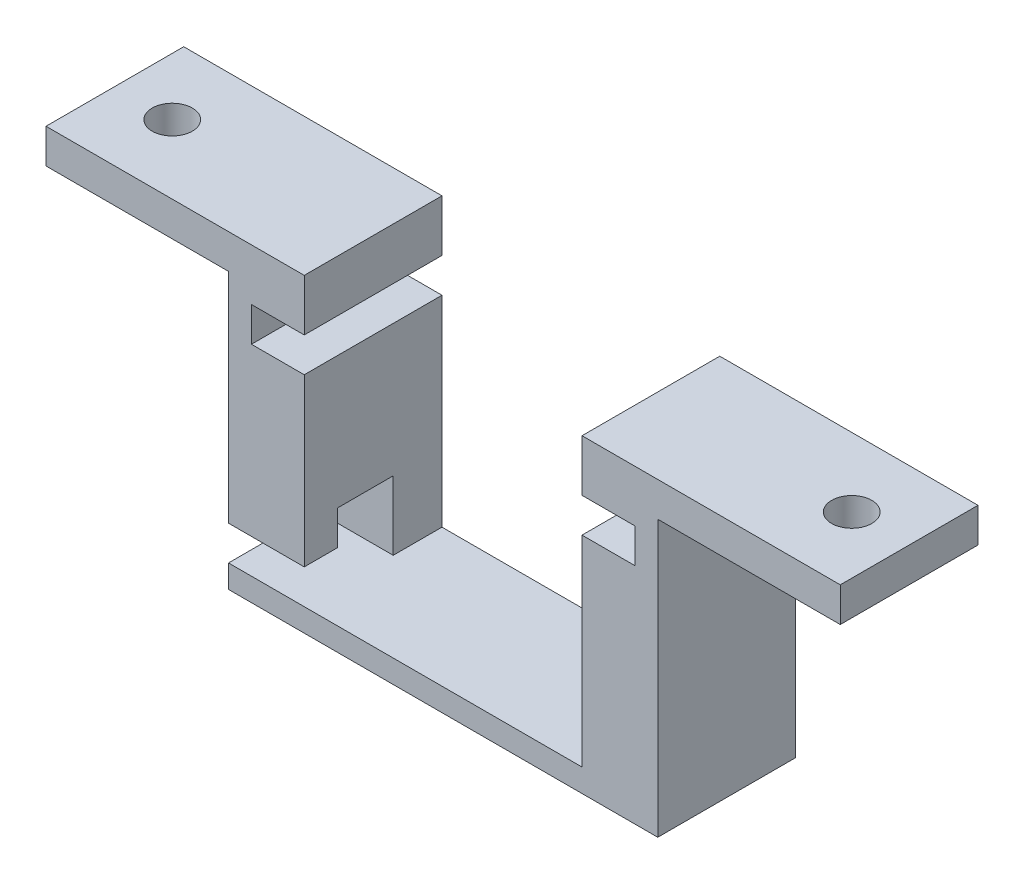
SolidWorks part; units mm, degrees
ref_plane "Alzado" through (0, 0, 0) normal (0, 0, 1) x (1, 0, 0)
ref_plane "Planta" through (0, 0, 0) normal (0, 1, 0) x (1, 0, 0)
ref_plane "Vista lateral" through (0, 0, 0) normal (1, 0, 0) x (0, 0, -1)
sketch "Croquis1" plane through (0, 0, 0) normal (0, 0, 1) x (1, 0, 0)
  line L0 (-12.1, 0) -> (12.1, 0)
  line L1 (-12.1, 0) -> (-12.1, 17.5)
  line L2 (-12.1, 17.5) -> (-16.7, 17.5)
  line L3 (-16.7, 17.5) -> (-16.7, 20.5)
  line L4 (-16.7, 20.5) -> (-12.1, 20.5)
  line L5 (-12.1, 20.5) -> (-12.1, 25)
  line L6 (12.1, 0) -> (12.1, 17.5)
  line L7 (12.1, 17.5) -> (16.7, 17.5)
  line L8 (16.7, 17.5) -> (16.7, 20.5)
  line L9 (16.7, 20.5) -> (12.1, 20.5)
  line L10 (12.1, 20.5) -> (12.1, 25)
  line L14 (-18.7, 25) -> (-18.7, -2)
  line L15 (-18.7, -2) -> (18.7, -2)
  line L16 (18.7, -2) -> (18.7, 25)
  line L17 (-12.1, 25) -> (-18.7, 25)
  line L18 (12.1, 25) -> (18.7, 25)
  point P4 (0, 0)
  point P20 (16.7, 19)
  dimension "D1" = 24.2
  dimension "D2" = 17.5
  dimension "D3" = 4.6
  dimension "D4" = 3
  dimension "D6" = 4.5
  dimension "D8" = 2
  dimension "D9" = 2
  dimension "D10" = 2
  dimension "D11" = 4.6
extrude "Saliente-Extruir1" add sketch "Croquis1" along normal blind 12
sketch "Croquis2" plane through (0, 25, 0) normal (0, 1, 0) x (1, 0, 0)
  line L0 (-12.1, -12) -> (-12.1, 0) construction
  line L1 (-12.1, -12) -> (-34.6, -12)
  line L2 (-12.1, -12) -> (-12.1, 0)
  line L3 (-12.1, 0) -> (-34.6, 0)
  line L4 (-34.6, -12) -> (-34.6, 0)
  line L6 (12.1, -12) -> (34.6, -12)
  line L8 (12.1, 0) -> (34.6, 0)
  line L9 (34.6, -12) -> (34.6, 0)
  line L11 (12.1, -12) -> (12.1, 0)
  line L12 (-29.6, -6) -> (29.6, -6) construction
  circle A0 centre (-29.6, -6) radius 1.75
  circle A1 centre (29.6, -6) radius 1.75
  point P18 (12.1, -6)
  dimension "D1" = 3.5
  dimension "D4" = 3.5
  dimension "D5" = 5
  dimension "D2" = 17.5
  dimension "D3" = 17.5
  dimension "D6" = 5
sketch "Croquis3" plane through (-12.1, 0, 0) normal (1, 0, 0) x (0, 0, -1)
  line L1 (-4.25, 0) -> (-7.75, 0)
  line L2 (-4.25, 0) -> (-4.25, 6)
  line L3 (-4.25, 6) -> (-7.75, 6)
  line L4 (-7.75, 0) -> (-7.75, 6) construction
  line L5 (-12, 0) -> (0, 0) construction
  line L6 (-7.75, 6) -> (-12, 6)
  line L7 (-12, 0) -> (-12, 17.5) construction
  line L8 (-12, 6) -> (-12, 0)
  line L9 (-12, 0) -> (-7.75, 0)
  point P4 (-6, 0)
  point P7 (-6, 0)
  dimension "D1" = 3.5
  dimension "D2" = 6
extrude "Cortar-Extruir1" cut sketch "Croquis3" against normal blind 8
sketch "Croquis4" plane through (0, 6, 0) normal (0, -1, 0) x (1, 0, 0)
  line L0 (-12.1, 4.25) -> (-12.1, 12) construction
  line L1 (-18.7, 12) -> (-12.1, 12)
  line L2 (-18.7, 12) -> (-18.7, 9.1076)
  line L3 (-18.7, 9.1076) -> (-12.1, 9.1076)
  line L4 (-12.1, 12) -> (-12.1, 9.1076)
extrude "Saliente-Extruir3" add sketch "Croquis4" along normal blind 3
extrude "Saliente-Extruir4" add sketch "Croquis2" against normal blind 3
